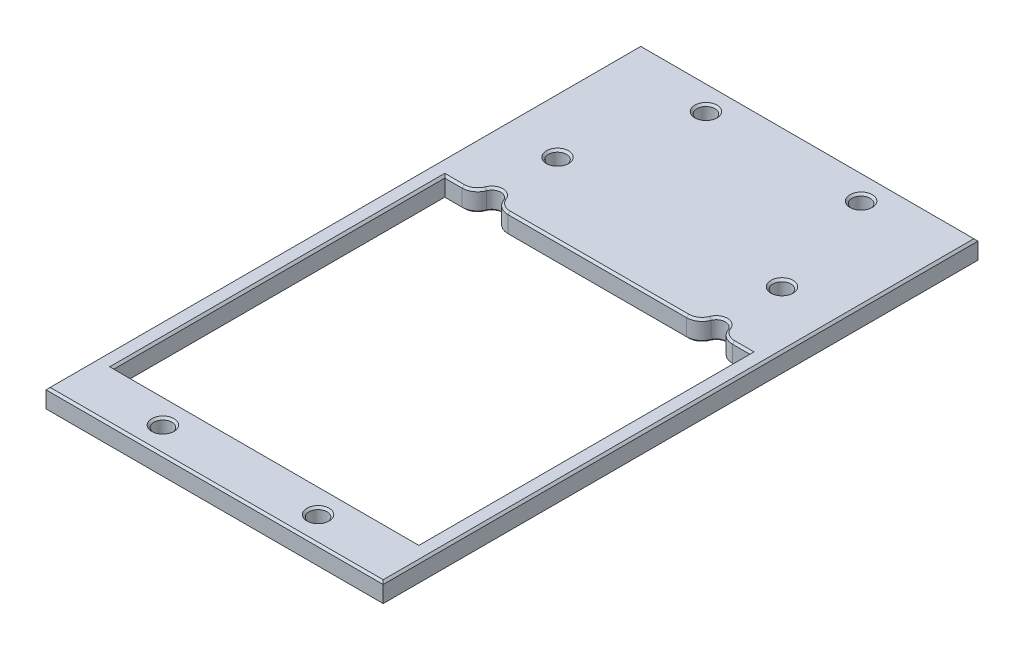
SolidWorks part; units mm, degrees
ref_plane "Front Plane" through (0, 0, 0) normal (0, 0, 1) x (1, 0, 0)
ref_plane "Top Plane" through (0, 0, 0) normal (0, 1, 0) x (1, 0, 0)
ref_plane "Right Plane" through (0, 0, 0) normal (1, 0, 0) x (0, 0, -1)
sketch "Sketch1" plane through (0, 0, 0) normal (0, 1, 0) x (1, 0, 0)
  line L0 (-29.5, 16.5) -> (-32.6, 16.5) construction
  line L1 (32.6, -57.5) -> (-32.6, -57.5)
  line L2 (32.6, -57.5) -> (32.6, 57.5)
  line L3 (32.6, 57.5) -> (-32.6, 57.5)
  line L4 (-32.6, -57.5) -> (-32.6, 57.5)
  line L5 (32.6, -57.5) -> (-32.6, 57.5) construction
  line L6 (32.6, 57.5) -> (-32.6, -57.5) construction
  line L7 (-29.5, -47.5) -> (29.5, -47.5)
  line L8 (-29.5, -47.5) -> (-29.5, 16.5)
  line L9 (-29.5, 16.5) -> (29.5, 16.5)
  line L10 (29.5, -47.5) -> (29.5, 16.5)
  line L11 (29.5, 16.5) -> (32.6, 16.5) construction
  line L12 (0, -57.5) -> (0, -47.5) construction
  line L13 (0, 57.5) -> (0, 47.5) construction
  line L14 (-15, 52.5) -> (15, 52.5) construction
  line L15 (-15, -52.5) -> (15, -52.5) construction
  circle A0 centre (-15, 52.5) radius 1.75
  circle A1 centre (15, 52.5) radius 1.75
  circle A2 centre (15, -52.5) radius 1.75
  circle A3 centre (-15, -52.5) radius 1.75
  point P0 (0, 0)
  point P20 (0, -52.5)
  point P21 (0, 52.5)
  dimension "D7" = 3.5
  dimension "D1" = 65.2
  dimension "D2" = 59
  dimension "D3" = 64
  dimension "D4" = 115
  dimension "D5" = 10
  dimension "D6" = 30
extrude "Boss-Extrude1" add sketch "Sketch1" along normal blind 4
sketch "Sketch2" plane through (0, 4, 0) normal (0, 1, 0) x (1, 0, 0)
  line L0 (-21.7, 30.5) -> (-21.7, 17.8) construction
  line L1 (21.7, 30.5) -> (21.7, 17.8) construction
  line L2 (0, 57.5) -> (0, 24.15) construction
  line L3 (32.6, 57.5) -> (-32.6, 57.5) construction
  line L4 (-21.7, 24.15) -> (21.7, 24.15) construction
  circle A0 centre (-21.7, 17.8) radius 1.75
  circle A1 centre (21.7, 17.8) radius 1.75
  circle A2 centre (21.7, 30.5) radius 1.75
  circle A3 centre (-21.7, 30.5) radius 1.75
  dimension "D4" = 3.5
  dimension "D1" = 12.7
  dimension "D2" = 43.4
  dimension "D3" = 27
extrude "Cut-Extrude1" cut sketch "Sketch2" against normal through all
fillet "Fillet1" radius 3 4 edges at (22.8715, 2, -16.5) (20.5285, 2, -16.5) (-20.5285, 2, -16.5) (-22.8715, 2, -16.5)
chamfer "Chamfer1" distance 0.4 angle 45 44 edges at (-15, 4, 54.25) (15, 4, -50.75) (0, 4, -57.5) (32.6, 4, 0) (0, 4, 57.5) (-32.6, 4, 0) (-15, 4, -50.75) (15, 4, 54.25) (21.7, 4, -28.75) (-21.7, 4, -28.75) (18.9645, 4, -17.0281) (0, 4, -16.5) (-18.9645, 4, -17.0281) (-21.7, 4, -19.55) (-24.4355, 4, -17.0281) (-27.8177, 4, -16.5) (-29.5, 4, 15.5) (0, 4, 47.5) (29.5, 4, 15.5) (27.8177, 4, -16.5) (24.4355, 4, -17.0281) (21.7, 4, -19.55) (-15, 0, 54.25) (15, 0, 54.25) (15, 0, -50.75) (-15, 0, -50.75) (29.5, 0, 15.5) (0, 0, 47.5) (-29.5, 0, 15.5) (-27.8177, 0, -16.5) (-24.4355, 0, -17.0281) (-21.7, 0, -19.55) (-18.9645, 0, -17.0281) (0, 0, -16.5) (18.9645, 0, -17.0281) (21.7, 0, -19.55) (24.4355, 0, -17.0281) (27.8177, 0, -16.5) (0, 0, 57.5) (32.6, 0, 0) (0, 0, -57.5) (-32.6, 0, 0) (21.7, 0, -28.75) (-21.7, 0, -28.75)
